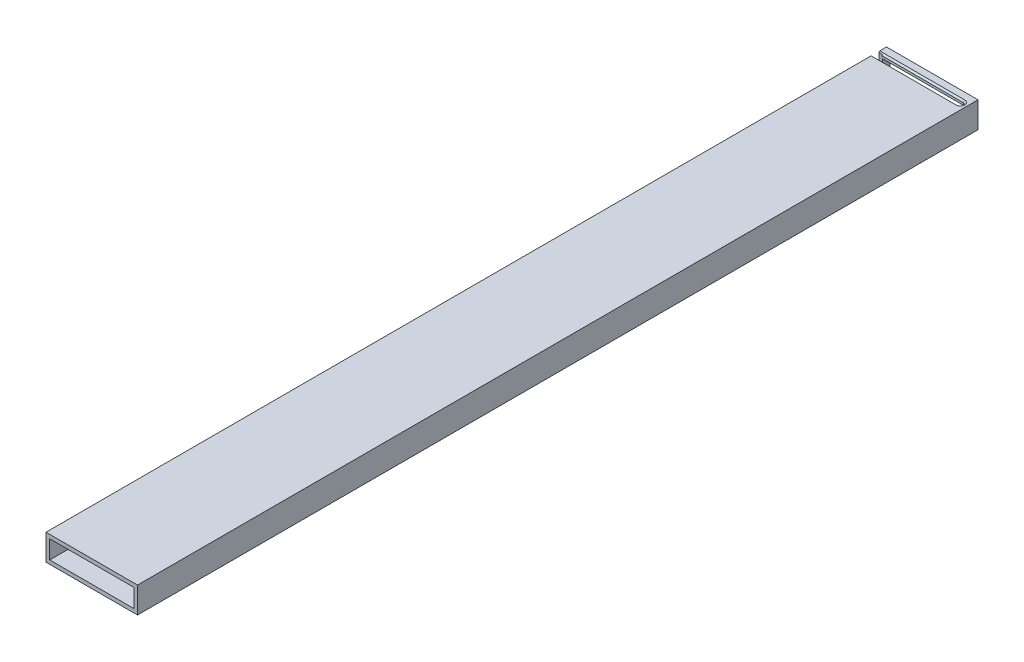
SolidWorks part; units mm, degrees
ref_plane "Piano frontale" through (0, 0, 0) normal (0, 0, 1) x (1, 0, 0)
ref_plane "Piano superiore" through (0, 0, 0) normal (0, 1, 0) x (1, 0, 0)
ref_plane "Piano destro" through (0, 0, 0) normal (1, 0, 0) x (0, 0, -1)
sketch "Schizzo1" plane through (0, 0, 0) normal (0, 0, 1) x (1, 0, 0)
  line L1 (-17.9659, 5.1) -> (17.9659, 5.1)
  line L2 (-17.9659, 5.1) -> (-17.9659, -5.1)
  line L3 (-17.9659, -5.1) -> (17.9659, -5.1)
  line L4 (17.9659, 5.1) -> (17.9659, -5.1)
  line L5 (-17.9659, 5.1) -> (17.9659, -5.1) construction
  line L6 (-17.9659, -5.1) -> (17.9659, 5.1) construction
  line L7 (-16.5, 3.6) -> (16.5, 3.6)
  line L8 (-16.5, 3.6) -> (-16.5, -3.6)
  line L9 (-16.5, -3.6) -> (16.5, -3.6)
  line L10 (16.5, 3.6) -> (16.5, -3.6)
  line L11 (-16.5, 3.6) -> (16.5, -3.6) construction
  line L12 (-16.5, -3.6) -> (16.5, 3.6) construction
  point P0 (0, 0)
  point P6 (0, 0)
  dimension "D1" = 1.5
  dimension "D2" = 7.2
  dimension "D3" = 33
extrude "Estrusione-Estrusione1" add sketch "Schizzo1" along normal blind 330
sketch "Schizzo3" plane through (-17.9659, 0, 0) normal (-1, 0, 0) x (0, 0, 1)
  line L0 (0, 0) -> (3, 0) construction
  line L2 (3, 3.6) -> (5.7, 3.6)
  line L3 (3, 3.6) -> (3, 0.4)
  line L4 (0, 3.6) -> (0, -3.6)
  line L5 (330, 3.6) -> (0, 3.6)
  line L6 (330, -3.6) -> (330, 3.6)
  line L7 (0, -3.6) -> (330, -3.6)
  line L8 (0, 3.6) -> (0, -3.6)
  line L9 (330, 3.6) -> (0, 3.6)
  line L10 (330, -3.6) -> (330, 3.6)
  line L11 (0, -3.6) -> (330, -3.6)
  line L12 (3, 0.4) -> (5.7, 0.4)
  line L13 (5.7, 3.6) -> (5.7, 0.4)
  dimension "D2" = 3
  dimension "D3" = 3.2
  dimension "D4" = 2.7
  dimension "D1" = 0
extrude "Taglio-Estrusione1" cut sketch "Schizzo3" against normal up to surface (34.4659 mm away) contours L13 L2 L3 L12 up to face at (16.5, 0, 165)
sketch "Schizzo4" plane through (0, 5.1, 0) normal (0, 1, 0) x (1, 0, 0)
  line L0 (-16.5, -4.35) -> (13.3, -4.35) construction
  line L1 (15.4, -5.45) -> (-17.9659, -5.45)
  line L2 (-17.9659, -330) -> (-17.9659, 0) construction
  line L3 (-17.9659, -5.45) -> (-17.9659, -3.25)
  line L4 (-16.5, -5.7) -> (-16.5, -3)
  line L5 (-16.5, -3) -> (-17.9659, -3)
  line L6 (-17.9659, -3) -> (-17.9659, -5.7)
  line L7 (-17.9659, -5.7) -> (-16.5, -5.7)
  line L8 (-16.5, -5.7) -> (-16.5, -3)
  line L9 (-16.5, -3) -> (-17.9659, -3)
  line L10 (-17.9659, -3) -> (-17.9659, -5.7)
  line L11 (-17.9659, -5.7) -> (-16.5, -5.7)
  line L12 (16.5, 0) -> (-16.5, 0)
  line L13 (-16.5, 0) -> (-16.5, -330)
  line L14 (-16.5, -330) -> (16.5, -330)
  line L15 (16.5, -330) -> (16.5, 0)
  line L16 (16.5, 0) -> (-16.5, 0)
  line L17 (-16.5, 0) -> (-16.5, -330)
  line L18 (-16.5, -330) -> (16.5, -330)
  line L19 (16.5, -330) -> (16.5, 0)
  line L20 (-17.9659, -3.25) -> (15.4, -3.25)
  arc A0 (15.4, -5.45) -> (15.4, -3.25) centre (15.4, -4.35) ccw
  dimension "D1" = 2.2
  dimension "D2" = 0
  dimension "D3" = 0
extrude "Taglio-Estrusione2" cut sketch "Schizzo4" against normal up to surface (1.5 mm away)
chamfer "Smusso2" distance 0.6 angle 45 3 edges at (-0.55, 5.1, 3.25) (16.5, 5.1, 4.35) (-0.55, 5.1, 5.45)
